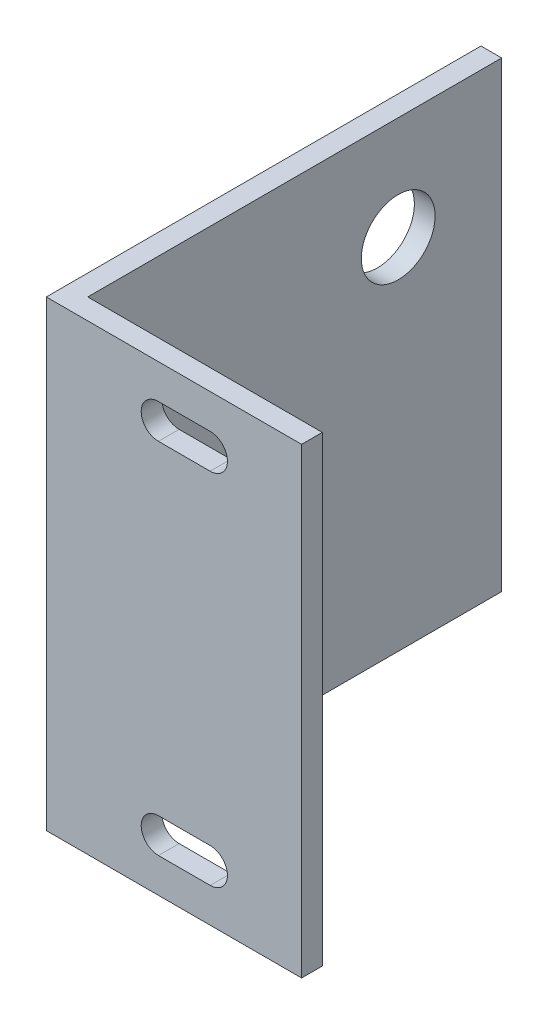
SolidWorks part; units mm, degrees
ref_plane "Front Plane" through (0, 0, 0) normal (0, 0, 1) x (1, 0, 0)
ref_plane "Top Plane" through (0, 0, 0) normal (0, 1, 0) x (1, 0, 0)
ref_plane "Right Plane" through (0, 0, 0) normal (1, 0, 0) x (0, 0, -1)
sketch "Sketch1" plane through (0, 0, 0) normal (0, 1, 0) x (1, 0, 0)
  line L0 (-18.5, 1.5) -> (-18.5, 61.5)
  line L1 (-15.5, 1.5) -> (18.5, 1.5)
  line L2 (-18.5, 1.5) -> (-18.5, -1.5)
  line L3 (-18.5, -1.5) -> (18.5, -1.5)
  line L4 (18.5, 1.5) -> (18.5, -1.5)
  line L5 (0, 0) -> (18.5, -1.5) construction
  line L6 (-18.5, -1.5) -> (18.5, 1.5) construction
  line L7 (-18.5, 61.5) -> (-15.5, 61.5)
  line L8 (-15.5, 61.5) -> (-15.5, 1.5)
  point P0 (0, 0)
  dimension "D1" = 37
  dimension "D2" = 3
  dimension "D3" = 3
  dimension "D4" = 60
extrude "Boss-Extrude1" add sketch "Sketch1" along normal blind 66.99 contours L4 L1 L2 L3 | L8 L7 L0 L1
sketch "Sketch2" plane through (-15.5, 0, 0) normal (1, 0, 0) x (0, 0, -1)
  line L0 (61.5, 0) -> (1.5, 0) construction
  line L1 (1.5, 66.99) -> (1.5, 0) construction
  line L2 (61.5, 66.99) -> (61.5, 0) construction
  line L4 (61.5, 66.99) -> (1.5, 66.99) construction
  circle A0 centre (16.5, 15) radius 5.35
  circle A1 centre (46.5, 51.9884) radius 5.35
  dimension "D1" = 10.7
  dimension "D2" = 15
  dimension "D3" = 15
  dimension "D4" = 10.7
  dimension "D5" = 47.625
  dimension "D6" = 15
extrude "Cut-Extrude1" cut sketch "Sketch2" against normal through all
sketch "Sketch3" plane through (0, 0, -1.5) normal (0, 0, -1) x (-1, 0, 0)
  line L0 (-5.25, 7.5) -> (2.25, 7.5) construction
  line L1 (-5.25, 10) -> (2.25, 10)
  line L2 (-5.25, 5) -> (2.25, 5)
  line L3 (-18.5, 66.99) -> (-18.5, 0) construction
  line L4 (15.5, 0) -> (-18.5, 0) construction
  line L6 (-18.5, 33.495) -> (-5.25, 33.495) construction
  line L7 (-5.25, 59.49) -> (2.25, 59.49) construction
  line L8 (-5.25, 56.99) -> (2.25, 56.99)
  line L9 (-5.25, 61.99) -> (2.25, 61.99)
  arc A0 (-5.25, 10) -> (-5.25, 5) centre (-5.25, 7.5) ccw
  arc A1 (2.25, 5) -> (2.25, 10) centre (2.25, 7.5) ccw
  arc A2 (-5.25, 56.99) -> (-5.25, 61.99) centre (-5.25, 59.49) cw
  arc A3 (2.25, 61.99) -> (2.25, 56.99) centre (2.25, 59.49) cw
  point P2 (-1.5, 7.5)
  point P15 (-1.5, 59.49)
  dimension "D1" = 2.5
  dimension "D3" = 13.25
  dimension "D2" = 7.5
  dimension "D4" = 7.5
extrude "Cut-Extrude2" cut sketch "Sketch3" against normal through all
